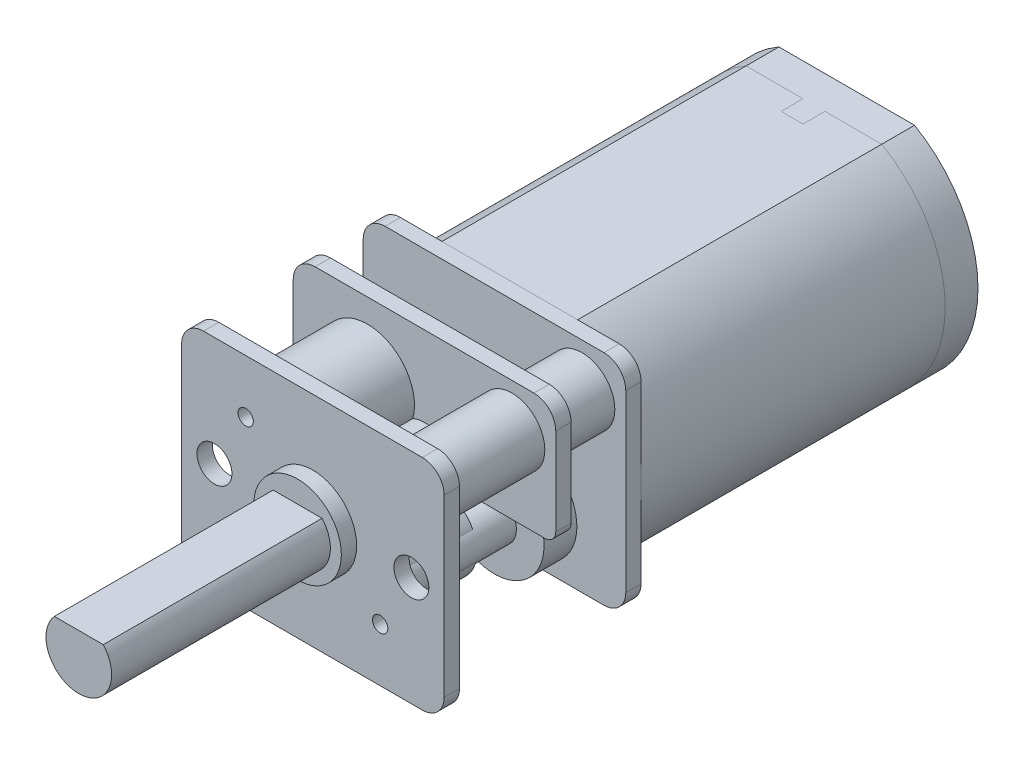
SolidWorks part; units mm, degrees
other "back"
other "motor"
other "gearbox"
other "front_shaft"
other "terminal1"
other "terminal2"
other "gears"
ref_plane "Přední rovina" through (0, 0, 0) normal (0, 0, 1) x (1, 0, 0)
ref_plane "Horní rovina" through (0, 0, 0) normal (0, 1, 0) x (1, 0, 0)
ref_plane "Pravá rovina" through (0, 0, 0) normal (1, 0, 0) x (0, 0, -1)
sketch "Skica1" plane through (0, 0, 0) normal (0, 0, 1) x (1, 0, 0)
  line L1 (-3.1, 5) -> (3.1, 5)
  line L3 (-3.1, -5) -> (3.1, -5)
  line L5 (0, -5) -> (0, 5) construction
  arc A0 (-3.1, 5) -> (-3.1, -5) centre (-0.2397, 0) ccw
  arc A1 (3.1, 5) -> (3.1, -5) centre (0.2397, 0) cw
  dimension "D1" = 12
  dimension "D2" = 10
  dimension "D3" = 6.2
extrude "Přidat vysunutím1" add sketch "Skica1" against normal blind 15.4
sketch "Skica2" plane through (0, 0, -15.4) normal (0, 0, -1) x (-1, 0, 0)
  circle A0 centre (0, 0) radius 2.5
  dimension "D1" = 5
extrude "Přidat vysunutím2" add sketch "Skica2" along normal blind 0.8
sketch "Skica3" plane through (0, 0, 0) normal (0, 1, 0) x (1, 0, 0)
  line L0 (-6, 13.9) -> (-0.5, 13.9)
  line L1 (-6, 15.4) -> (-6, 0) construction
  line L2 (-0.5, 13.9) -> (-0.5, 12.9)
  line L3 (-0.5, 12.9) -> (0.5, 12.9)
  line L4 (0, 0) -> (0, 16.7322) construction
  line L5 (3.1, 15.4) -> (-3.1, 15.4) construction
  line L6 (0.5, 13.9) -> (0.5, 12.9)
  line L7 (6, 13.9) -> (0.5, 13.9)
  point P12 (0, 12.9)
  dimension "D1" = 1.5
  dimension "D2" = 1
  dimension "D3" = 1
split "Rozdělit1" trim tools "Skica3" bodies to split 102 resulting bodies 103 104
sketch "Skica5" plane through (0, 0, -16.2) normal (0, 0, -1) x (-1, 0, 0)
  circle A0 centre (0, 0) radius 0.5
  dimension "D1" = 1
extrude "Přidat vysunutím3" [suppressed] add sketch "Skica5" along normal blind 5 separate body
sketch "Skica6" plane through (0, 0, 0) normal (0, 0, 1) x (1, 0, 0)
  line L0 (-3.1, -5) -> (3.1, -5) construction
  line L1 (-5, 5) -> (5, 5)
  line L2 (-6, 4) -> (-6, -4)
  line L3 (-5, -5) -> (5, -5)
  line L4 (6, 4) -> (6, -4)
  line L5 (3.1, 5) -> (-3.1, 5) construction
  arc A0 (-3.1, 5) -> (-3.1, -5) centre (-0.2397, 0) ccw construction
  arc A1 (3.1, -5) -> (3.1, 5) centre (0.2397, 0) ccw construction
  arc A2 (5, -5) -> (6, -4) centre (5, -4) ccw
  arc A3 (-6, -4) -> (-5, -5) centre (-5, -4) ccw
  arc A4 (5, 5) -> (6, 4) centre (5, 4) cw
  arc A5 (-5, 5) -> (-6, 4) centre (-5, 4) ccw
  dimension "D1" = 1
  dimension "D2" = 1
  dimension "D3" = 1
  dimension "D4" = 1
extrude "Přidat vysunutím4" add sketch "Skica6" along normal blind 0.7 separate body
sketch "Skica8" plane through (0, 0, 0.7) normal (0, 0, 1) x (1, 0, 0)
  line L1 (-6, 4) -> (-6, -4) construction
  line L2 (-5, -5) -> (5, -5) construction
  line L3 (6, -4) -> (6, 4) construction
  line L4 (5, 5) -> (-5, 5) construction
  circle A0 centre (4, 3) radius 1.5
  circle A1 centre (-4, -3) radius 1.5
  dimension "D1" = 3
  dimension "D3" = 2
  dimension "D2" = 2
  dimension "D4" = 2
  dimension "D5" = 2
extrude "Přidat vysunutím6" add sketch "Skica8" along normal blind 2.5
sketch "Skica9" plane through (0, 0, 3.2) normal (0, 0, 1) x (1, 0, 0)
  line L0 (5.5, -0.5) -> (1.5, -0.5)
  line L1 (-0.5, -2.5) -> (-0.5, -4.5)
  line L4 (6, -4) -> (6, 4)
  line L5 (5, 5) -> (-5, 5)
  line L6 (-6, 4) -> (-6, -4)
  line L7 (-5, -5) -> (5, -5)
  line L8 (6, 0) -> (6, 4)
  line L9 (5, 5) -> (-5, 5)
  line L10 (-6, 4) -> (-6, -4)
  line L11 (-5, -5) -> (-1, -5)
  arc A0 (5.5, -0.5) -> (6, 0) centre (5.5, 0) ccw
  arc A1 (1.5, -0.5) -> (-0.5, -2.5) centre (1.5, -2.5) ccw
  arc A2 (-0.5, -4.5) -> (-1, -5) centre (-1, -4.5) cw
  arc A4 (5, -5) -> (6, -4) centre (5, -4) ccw
  arc A5 (6, 4) -> (5, 5) centre (5, 4) ccw
  arc A6 (-5, 5) -> (-6, 4) centre (-5, 4) ccw
  arc A7 (-6, -4) -> (-5, -5) centre (-5, -4) ccw
  arc A9 (6, 4) -> (5, 5) centre (5, 4) ccw
  arc A10 (-5, 5) -> (-6, 4) centre (-5, 4) ccw
  arc A11 (-6, -4) -> (-5, -5) centre (-5, -4) ccw
  point P17 (6, -0.5)
  point P20 (-0.5, -0.5)
  point P23 (-0.5, -5)
  dimension "D4" = 0.5
  dimension "D5" = 2
  dimension "D6" = 0.5
  dimension "D2" = 6.5
  dimension "D3" = 4.5
  dimension "D1" = 0
extrude "Přidat vysunutím7" add sketch "Skica9" along normal blind 0.7
sketch "Skica10" plane through (0, 0, 3.9) normal (0, 0, 1) x (1, 0, 0)
  circle A0 centre (-4, -3) radius 1.5 construction
  circle A1 centre (4, 3) radius 1.5 construction
  circle A2 centre (-4, -3) radius 1.5
  circle A3 centre (4, 3) radius 1.5
extrude "Přidat vysunutím8" add sketch "Skica10" along normal offset from surface (4.4 mm away) 8.3 up to face at (0, 0, 0)
sketch "Skica11" plane through (0, 0, 8.3) normal (0, 0, 1) x (1, 0, 0)
  line L4 (6, -4) -> (6, 4)
  line L5 (5, 5) -> (-5, 5)
  line L6 (-6, 4) -> (-6, -4)
  line L7 (-5, -5) -> (5, -5)
  line L8 (6, -4) -> (6, 4)
  line L9 (5, 5) -> (-5, 5)
  line L10 (-6, 4) -> (-6, -4)
  line L11 (-5, -5) -> (5, -5)
  arc A4 (5, -5) -> (6, -4) centre (5, -4) ccw
  arc A5 (6, 4) -> (5, 5) centre (5, 4) ccw
  arc A6 (-5, 5) -> (-6, 4) centre (-5, 4) ccw
  arc A7 (-6, -4) -> (-5, -5) centre (-5, -4) ccw
  arc A8 (5, -5) -> (6, -4) centre (5, -4) ccw
  arc A9 (6, 4) -> (5, 5) centre (5, 4) ccw
  arc A10 (-5, 5) -> (-6, 4) centre (-5, 4) ccw
  arc A11 (-6, -4) -> (-5, -5) centre (-5, -4) ccw
  dimension "D1" = 0
extrude "Přidat vysunutím9" add sketch "Skica11" along normal blind 0.7
sketch "Skica12" plane through (0, 0, 9) normal (0, 0, 1) x (1, 0, 0)
  circle A0 centre (0, 0) radius 2
  dimension "D1" = 4
extrude "Přidat vysunutím10" add sketch "Skica12" along normal blind 0.7
sketch "Skica13" plane through (0, 0, 9.7) normal (0, 0, 1) x (1, 0, 0)
  line L0 (-1.118, 1) -> (1.118, 1)
  arc A0 (-1.118, 1) -> (1.118, 1) centre (0, 0) ccw
  dimension "D1" = 3
  dimension "D2" = 2.5
extrude "Přidat vysunutím11" add sketch "Skica13" along normal blind 10 separate body
sketch "Skica14" plane through (0, 0, 9) normal (0, 0, 1) x (1, 0, 0)
  line L0 (0, 0) -> (0, 7.3371) construction
  circle A0 centre (-4.5, 0) radius 0.8
  circle A1 centre (4.5, 0) radius 0.8
  dimension "D2" = 1.6
  dimension "D1" = 4.5
extrude "Odebrat vysunutím1" cut sketch "Skica14" against normal up to next (0.7 mm away)
sketch "Skica15" plane through (0, 0, 9) normal (0, 0, 1) x (1, 0, 0)
  line L0 (-6, 5) -> (6, -5) construction
  line L1 (6, -4) -> (6, 4) construction
  line L2 (-5, -5) -> (5, -5) construction
  line L3 (5, 5) -> (-5, 5) construction
  line L4 (-6, 4) -> (-6, -4) construction
  line L5 (0, 0) -> (2.9052, 3.4862) construction
  circle A0 centre (-3.0729, 2.5607) radius 0.35
  circle A1 centre (3.0729, -2.5607) radius 0.35
  dimension "D1" = 0.7
  dimension "D2" = 4
extrude "Odebrat vysunutím2" cut sketch "Skica15" against normal up to next (0.7 mm away)
ref_plane "Rovina2" through (3.1, 0, 0) normal (1, 0, 0) x (0, 0, -1)
sketch "Skica16" plane through (3.1, 0, 0) normal (1, 0, 0) x (0, 0, -1)
  line L0 (15.4, 1) -> (16.2, 1)
  line L1 (15.4, -2.5) -> (15.4, 2.5) construction
  line L2 (16.2, -1) -> (15.4, -1)
  line L3 (15.4, -5) -> (15.4, 5) construction
  line L4 (15.4, -1) -> (15.4, 1)
  arc A0 (16.2, 1) -> (16.2, -1) centre (16.2, 0) cw
  circle A1 centre (16.2, 0) radius 0.4
  dimension "D3" = 0.8
  dimension "D1" = 2
  dimension "D2" = 1.8
extrude "Přidat vysunutím12" add sketch "Skica16" along normal blind 0.5 separate body
mirror "Zrcadlit2" about plane through (0, 0, 0) normal (1, 0, 0) of bodies 121
sketch "Skica17" plane through (0, 0, 0.7) normal (0, 0, 1) x (1, 0, 0)
  line L0 (0.3859, -0.6431) -> (0.3344, -0.5574)
  circle A0 centre (0, 0) radius 0.75
  circle A1 centre (1.5, -2.5) radius 2.2655
  arc A2 (1.5, -0.5) -> (-0.5, -2.5) centre (1.5, -2.5) ccw construction
  dimension "D1" = 1.5
  dimension "D2" = 0.1
extrude "Přidat vysunutím13" add sketch "Skica17" along normal blind 1.5 separate body contours A0 | A1
sketch "Skica18" plane through (0, 0, 2.2) normal (0, 0, 1) x (1, 0, 0)
  circle A0 centre (1.5, -2.5) radius 1
  dimension "D1" = 2
extrude "Přidat vysunutím15" add sketch "Skica18" along normal up to next
sketch "Skica19" plane through (0, 0, 3.9) normal (0, 0, 1) x (1, 0, 0)
  arc A1 (-0.5304, 1.2263) -> (-1.3352, 0.0482) centre (-2.6038, 1.7788) ccw
  arc A2 (-0.3871, -1.2788) -> (0.9802, -0.908) centre (0.7013, -2.586) ccw
  arc A3 (-1.3352, 0.0482) -> (-0.3871, -1.2788) centre (0, 0) ccw
  arc A4 (0.9802, -0.908) -> (-0.5304, 1.2263) centre (0, 0) ccw
extrude "Přidat vysunutím16" add sketch "Skica19" along normal up to surface (4.4 mm away) up to face at (3.4229, -2.5607, 8.3)
sketch "Skica20" plane through (0, 0, 0) normal (0, 0, 1) x (1, 0, 0)
  circle A0 centre (0, 0) radius 3.6
  dimension "D1" = 7.2
extrude "Odebrat vysunutím3" cut sketch "Skica20" against normal through all
sketch "Skica21" plane through (0, 0, 0) normal (1, 0, 0) x (0, 0, -1)
  line L0 (0, 0) -> (-2.95, 0) construction
  line L1 (-2.95, 0) -> (-2.2, 0.75)
  line L2 (-2.2, 0.75) -> (-2.2, 0)
  line L3 (-2.2, 0.75) -> (-2.2, -0.75) construction
  line L4 (-2.2, 0) -> (-2.95, 0)
  dimension "D1" = 45
revolve "Rotovat1" add sketch "Skica21" angle 360 about L0
